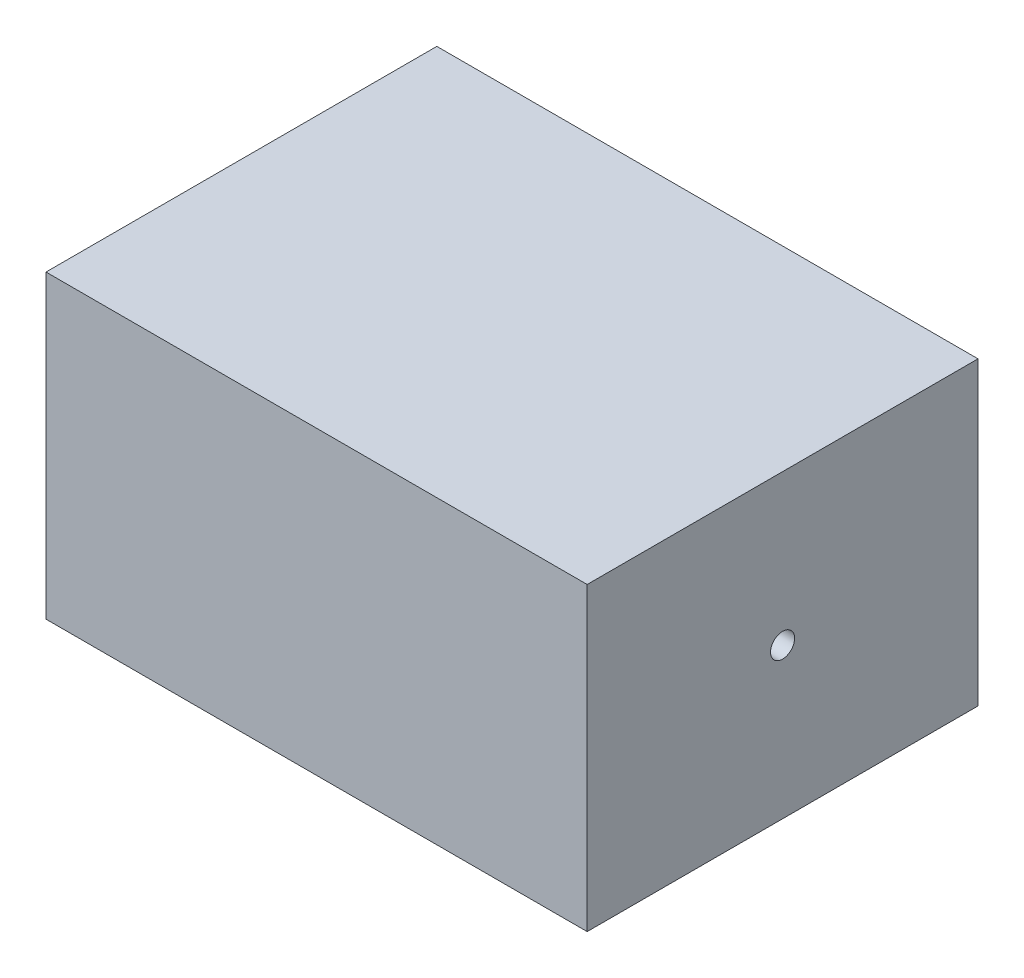
SolidWorks part; units mm, degrees
ref_plane "前视基准面" through (0, 0, 0) normal (0, 0, 1) x (1, 0, 0)
ref_plane "上视基准面" through (0, 0, 0) normal (0, 1, 0) x (1, 0, 0)
ref_plane "右视基准面" through (0, 0, 0) normal (1, 0, 0) x (0, 0, -1)
sketch "草图1" plane through (0, 0, 0) normal (0, 0, 1) x (1, 0, 0)
  line L1 (-44.7115, 29.5673) -> (45.2885, 29.5673)
  line L2 (-44.7115, 29.5673) -> (-44.7115, -20.4327)
  line L3 (-44.7115, -20.4327) -> (45.2885, -20.4327)
  line L4 (45.2885, 29.5673) -> (45.2885, -20.4327)
  dimension "D1" = 90
  dimension "D2" = 50
extrude "凸台-拉伸1" add sketch "草图1" along normal blind 65
sketch "草图2" plane through (-44.7115, 0, 0) normal (-1, 0, 0) x (0, 0, 1)
  line L0 (65, 29.5673) -> (65, -20.4327) construction
  line L1 (65, 29.5673) -> (0, 29.5673) construction
  circle A0 centre (32.5, 4.5673) radius 2
  dimension "D1" = 4
  dimension "D2" = 32.5
  dimension "D3" = 25
extrude "切除-拉伸1" cut sketch "草图2" against normal through all
